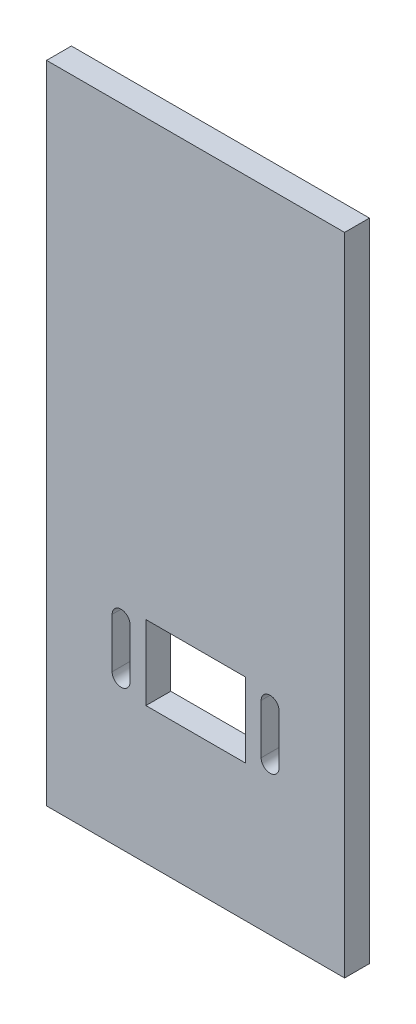
SolidWorks part; units mm, degrees
material "Glass"
ref_plane "Front Plane" through (0, 0, 0) normal (0, 0, 1) x (1, 0, 0)
ref_plane "Top Plane" through (0, 0, 0) normal (0, 1, 0) x (1, 0, 0)
ref_plane "Right Plane" through (0, 0, 0) normal (1, 0, 0) x (0, 0, -1)
sketch "Sketch1" plane through (0, 0, 0) normal (0, 0, 1) x (1, 0, 0)
  line L1 (-30, 65) -> (30, 65)
  line L2 (-30, 65) -> (-30, -65)
  line L3 (-30, -65) -> (30, -65)
  line L4 (30, 65) -> (30, -65)
  line L5 (-30, 65) -> (30, -65) construction
  line L6 (-30, -65) -> (30, 65) construction
  point P0 (0, 0)
  dimension "D1" = 130
  dimension "D2" = 60
extrude "Boss-Extrude1" add sketch "Sketch1" along normal blind 5
sketch "Sketch2" plane through (0, 0, 0) normal (0, 0, -1) x (-1, 0, 0)
  line L0 (0, -30) -> (0, 0) construction
  line L1 (-10, -22.5) -> (10, -22.5)
  line L2 (-10, -22.5) -> (-10, -37.5)
  line L3 (-10, -37.5) -> (10, -37.5)
  line L4 (10, -22.5) -> (10, -37.5)
  line L5 (-10, -22.5) -> (10, -37.5) construction
  line L6 (-10, -37.5) -> (10, -22.5) construction
  point P0 (0, -30)
  dimension "D1" = 20
  dimension "D2" = 15
  dimension "D3" = 30
extrude "Cut-Extrude1" cut sketch "Sketch2" against normal up to surface (5 mm away) up to face at (0, 0, 5)
sketch "Sketch3" plane through (0, 0, 0) normal (0, 0, -1) x (-1, 0, 0)
  line L0 (15, -25) -> (15, -35) construction
  line L1 (16.8, -25) -> (16.8, -35)
  line L2 (13.2, -25) -> (13.2, -35)
  line L3 (-15, -25) -> (-15, -35) construction
  line L4 (-13.2, -25) -> (-13.2, -35)
  line L5 (-16.8, -25) -> (-16.8, -35)
  line L6 (-15, -30) -> (-10, -30) construction
  line L7 (-10, -22.5) -> (-10, -37.5) construction
  line L8 (-10, -30) -> (10, -30) construction
  line L9 (10, -37.5) -> (10, -22.5) construction
  line L10 (10, -30) -> (15, -30) construction
  line L11 (-10, -30) -> (-10, -37.5) construction
  arc A0 (16.8, -25) -> (13.2, -25) centre (15, -25) ccw
  arc A1 (13.2, -35) -> (16.8, -35) centre (15, -35) ccw
  arc A2 (-13.2, -25) -> (-16.8, -25) centre (-15, -25) ccw
  arc A3 (-16.8, -35) -> (-13.2, -35) centre (-15, -35) ccw
  point P2 (15, -30)
  point P7 (-15, -30)
  dimension "D2" = 1.8
  dimension "D1" = 5
  dimension "D3" = 10
extrude "Cut-Extrude2" cut sketch "Sketch3" against normal up to surface (5 mm away) up to face at (0, -30, 5)
